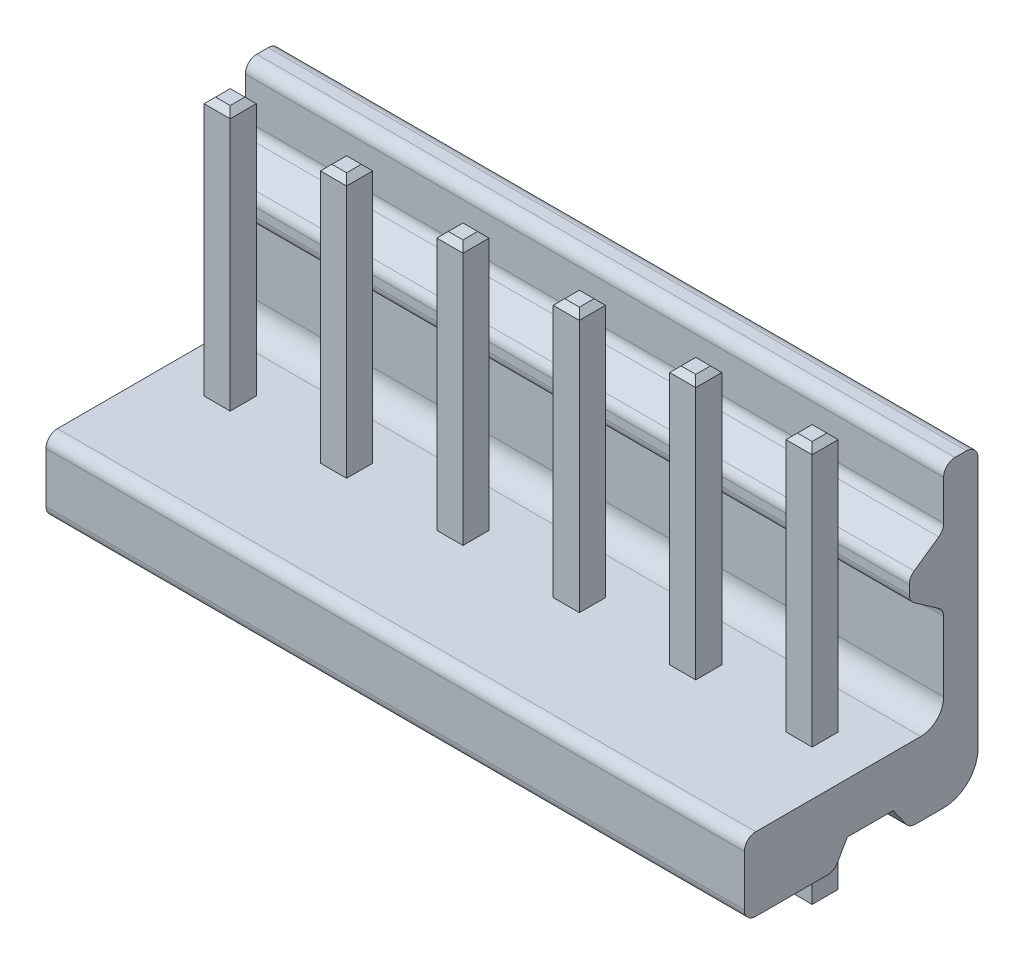
SolidWorks part; units mm, degrees
ref_plane "Ön Düzlem" through (0, 0, 0) normal (0, 0, 1) x (1, 0, 0)
ref_plane "Üst Düzlem" through (0, 0, 0) normal (0, 1, 0) x (1, 0, 0)
ref_plane "Sağ Düzlem" through (0, 0, 0) normal (1, 0, 0) x (0, 0, -1)
sketch "Sketch1" plane through (0, 0, 0) normal (1, 0, 0) x (0, 0, -1)
  line L0 (0, 2.7) -> (0, 0.5)
  line L1 (0.5, 0) -> (3.634, 0)
  line L2 (4.067, 0.25) -> (4.5, 1)
  line L3 (4.5, 1) -> (6.5, 1)
  line L4 (6.5, 1) -> (7.0509, 0.2132)
  line L5 (7.4605, 0) -> (8.7, 0)
  line L6 (10.2, 1.5) -> (10.2, 12.5)
  line L7 (9.7, 13) -> (9.2, 13)
  line L8 (0.5, 3.2) -> (7.7, 3.2)
  line L9 (8.7, 12.5) -> (8.7, 10.7603)
  line L10 (8.4868, 10.3507) -> (7.4132, 9.599)
  line L11 (7.2, 9.1894) -> (7.2, 8.8106)
  line L12 (7.4132, 8.401) -> (8.4868, 7.6493)
  line L13 (8.7, 7.2397) -> (8.7, 4.2)
  arc A0 (8.7, 0) -> (10.2, 1.5) centre (8.7, 1.5) ccw
  arc A1 (7.0509, 0.2132) -> (7.4605, 0) centre (7.4605, 0.5) ccw
  arc A2 (0, 2.7) -> (0.5, 3.2) centre (0.5, 2.7) cw
  arc A3 (0, 0.5) -> (0.5, 0) centre (0.5, 0.5) ccw
  arc A4 (3.634, 0) -> (4.067, 0.25) centre (3.634, 0.5) ccw
  arc A5 (8.7, 10.7603) -> (8.4868, 10.3507) centre (8.2, 10.7603) cw
  arc A6 (8.4868, 7.6493) -> (8.7, 7.2397) centre (8.2, 7.2397) cw
  arc A7 (7.2, 8.8106) -> (7.4132, 8.401) centre (7.7, 8.8106) ccw
  arc A8 (7.4132, 9.599) -> (7.2, 9.1894) centre (7.7, 9.1894) ccw
  arc A9 (10.2, 12.5) -> (9.7, 13) centre (9.7, 12.5) ccw
  arc A10 (9.2, 13) -> (8.7, 12.5) centre (9.2, 12.5) ccw
  arc A11 (8.7, 4.2) -> (7.7, 3.2) centre (7.7, 4.2) cw
  point P9 (5.5, 1)
  point P14 (10.2, 0)
  point P23 (0, 3.2)
  point P26 (0, 0)
  point P31 (8.7, 10.5)
  point P34 (8.7, 7.5)
  point P41 (10.2, 13)
  dimension "D10" = 1.5
  dimension "D11" = 0.5
  dimension "D16" = 1
  dimension "D1" = 3.2
  dimension "D2" = 10.2
  dimension "D3" = 120
  dimension "D4" = 235
  dimension "D5" = 1
  dimension "D6" = 2
  dimension "D7" = 5.5
  dimension "D8" = 13
  dimension "D9" = 1.5
  dimension "D12" = 1.5
  dimension "D13" = 125
  dimension "D14" = 3
  dimension "D15" = 2.5
extrude "Boss-Extrude1" add sketch "Sketch1" along normal blind 30.48
ref_plane "Plane1" through (0, -3, 0) normal (0, -1, 0) x (-1, 0, 0)
sketch "Sketch2" plane through (0, -3, 0) normal (0, -1, 0) x (-1, 0, 0)
  line L0 (-30.48, 0) -> (0, 0) construction
  line L1 (-28.51, 6.07) -> (-27.37, 6.07)
  line L2 (-28.51, 6.07) -> (-28.51, 4.93)
  line L3 (-28.51, 4.93) -> (-27.37, 4.93)
  line L4 (-27.37, 6.07) -> (-27.37, 4.93)
  line L5 (-28.51, 6.07) -> (-27.37, 4.93) construction
  line L6 (-28.51, 4.93) -> (-27.37, 6.07) construction
  line L7 (-30.48, 4.5) -> (-30.48, 6.5) construction
  point P0 (-27.94, 5.5)
  dimension "D1" = 1.14
  dimension "D2" = 1.14
  dimension "D3" = 5.5
  dimension "D4" = 2.54
extrude "Boss-Extrude2" add sketch "Sketch2" against normal blind 17.5
chamfer "Chamfer1" distance 0.25 angle 45 4 edges at (27.94, -3, -4.93) (28.51, -3, -5.5) (27.94, -3, -6.07) (27.37, -3, -5.5)
chamfer "Chamfer2" distance 0.25 angle 45 4 edges at (27.94, 14.5, -6.07) (28.51, 14.5, -5.5) (27.94, 14.5, -4.93) (27.37, 14.5, -5.5)
pattern_linear "LPattern3" count 6 spacing 5.08 along (-1, 0, 0) of "Chamfer2", "Chamfer1", "Boss-Extrude2"
